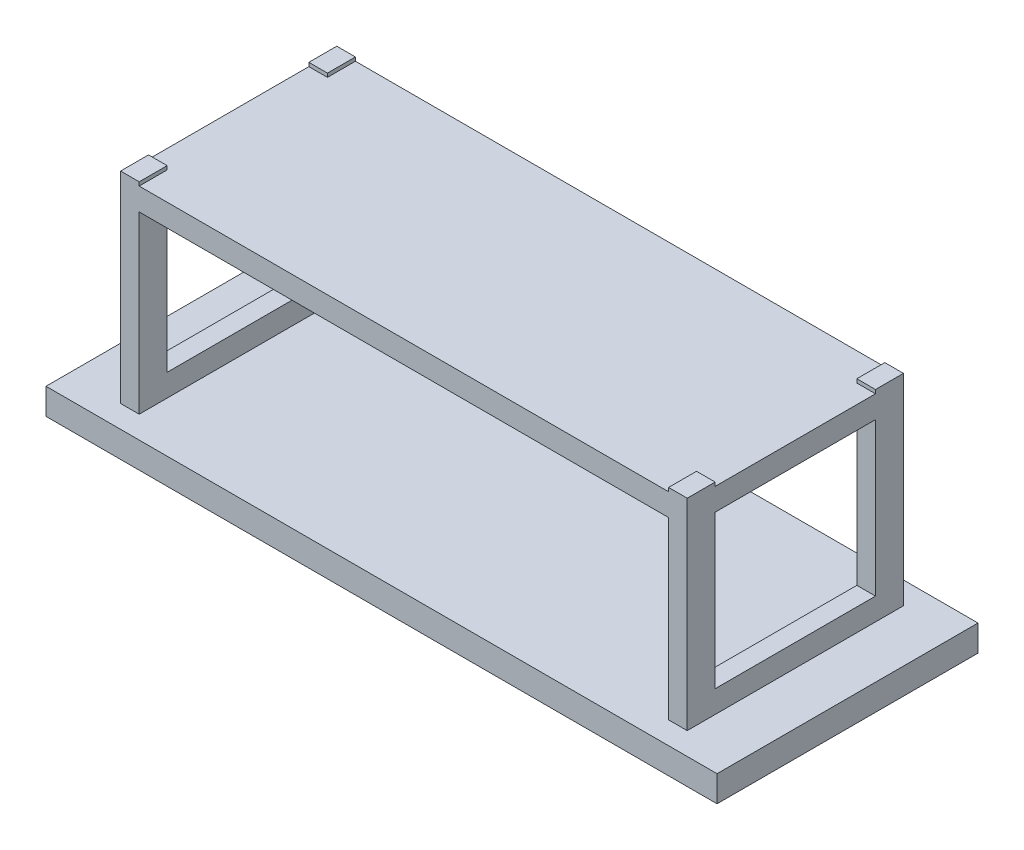
SolidWorks part; units mm, degrees
ref_plane "正面" through (0, 0, 0) normal (0, 0, 1) x (1, 0, 0)
ref_plane "平面" through (0, 0, 0) normal (0, 1, 0) x (1, 0, 0)
ref_plane "右側面" through (0, 0, 0) normal (1, 0, 0) x (0, 0, -1)
sketch "ｽｹｯﾁ1" plane through (0, 0, 0) normal (0, 1, 0) x (1, 0, 0)
  line L1 (0, 0) -> (1800, 0)
  line L2 (0, 0) -> (0, 700)
  line L3 (0, 700) -> (1800, 700)
  line L4 (1800, 0) -> (1800, 700)
  dimension "D1" = 1800
  dimension "D2" = 700
extrude "ﾎﾞｽ - 押し出し1" add sketch "ｽｹｯﾁ1" along normal blind 70
sketch "ｽｹｯﾁ2" plane through (0, 70, 0) normal (0, 1, 0) x (1, 0, 0)
  line L0 (1800, 700) -> (0, 700) construction
  line L1 (140, 640) -> (190, 640)
  line L2 (140, 640) -> (140, 60)
  line L3 (140, 60) -> (190, 60)
  line L4 (190, 640) -> (190, 60)
  line L5 (1660, 640) -> (1610, 640)
  line L6 (1660, 640) -> (1660, 60)
  line L7 (1660, 60) -> (1610, 60)
  line L8 (1610, 640) -> (1610, 60)
  line L9 (0, 0) -> (1800, 0) construction
  line L10 (1800, 0) -> (1800, 700) construction
  line L11 (0, 700) -> (0, 0) construction
  dimension "D1" = 50
  dimension "D2" = 50
  dimension "D3" = 60
  dimension "D4" = 60
  dimension "D5" = 60
  dimension "D6" = 60
  dimension "D7" = 140
  dimension "D8" = 140
extrude "ﾎﾞｽ - 押し出し2" add sketch "ｽｹｯﾁ2" along normal blind 60
sketch "ｽｹｯﾁ3" plane through (0, 130, 0) normal (0, 1, 0) x (1, 0, 0)
  line L0 (190, 60) -> (190, 640) construction
  line L1 (140, 640) -> (190, 640)
  line L2 (140, 640) -> (140, 565)
  line L3 (140, 565) -> (190, 565)
  line L4 (190, 640) -> (190, 565)
  line L5 (1610, 640) -> (1610, 60) construction
  line L6 (140, 60) -> (190, 60)
  line L7 (140, 60) -> (140, 135)
  line L8 (140, 135) -> (190, 135)
  line L9 (190, 60) -> (190, 135)
  line L10 (1660, 640) -> (1610, 640)
  line L11 (1660, 640) -> (1660, 565)
  line L12 (1660, 565) -> (1610, 565)
  line L13 (1610, 640) -> (1610, 565)
  line L15 (1660, 60) -> (1610, 60)
  line L16 (1660, 60) -> (1660, 135)
  line L17 (1660, 135) -> (1610, 135)
  line L18 (1610, 60) -> (1610, 135)
  dimension "D1" = 75
  dimension "D2" = 75
  dimension "D3" = 75
  dimension "D4" = 75
extrude "ﾎﾞｽ - 押し出し3" add sketch "ｽｹｯﾁ3" along normal blind 480
sketch "ｽｹｯﾁ4" plane through (0, 0, -565) normal (0, 0, 1) x (1, 0, 0)
  line L0 (1660, 610) -> (1660, 130) construction
  line L1 (1660, 600) -> (1610, 600)
  line L2 (1660, 600) -> (1660, 540)
  line L3 (1660, 540) -> (1610, 540)
  line L4 (1610, 600) -> (1610, 540)
  line L5 (1610, 610) -> (1610, 130) construction
  line L6 (190, 610) -> (190, 130) construction
  line L7 (190, 600) -> (140, 600)
  line L8 (190, 600) -> (190, 540)
  line L9 (190, 540) -> (140, 540)
  line L10 (140, 600) -> (140, 540)
  line L11 (140, 610) -> (140, 130) construction
  line L12 (140, 610) -> (190, 610) construction
  line L13 (1610, 610) -> (1660, 610) construction
  dimension "D1" = 60
  dimension "D2" = 10
  dimension "D3" = 60
  dimension "D4" = 10
extrude "ﾎﾞｽ - 押し出し4" add sketch "ｽｹｯﾁ4" along normal up to next
sketch "ｽｹｯﾁ5" plane through (1610, 0, 0) normal (-1, 0, 0) x (0, 0, 1)
  line L0 (-135, 600) -> (-565, 600) construction
  line L1 (-60, 600) -> (-640, 600)
  line L2 (-60, 600) -> (-60, 540)
  line L3 (-60, 540) -> (-640, 540)
  line L4 (-640, 600) -> (-640, 540)
  line L5 (-135, 540) -> (-565, 540) construction
  line L6 (-60, 610) -> (-60, 70) construction
  line L7 (-640, 610) -> (-640, 70) construction
extrude "ﾎﾞｽ - 押し出し5" add sketch "ｽｹｯﾁ5" along normal up to next
